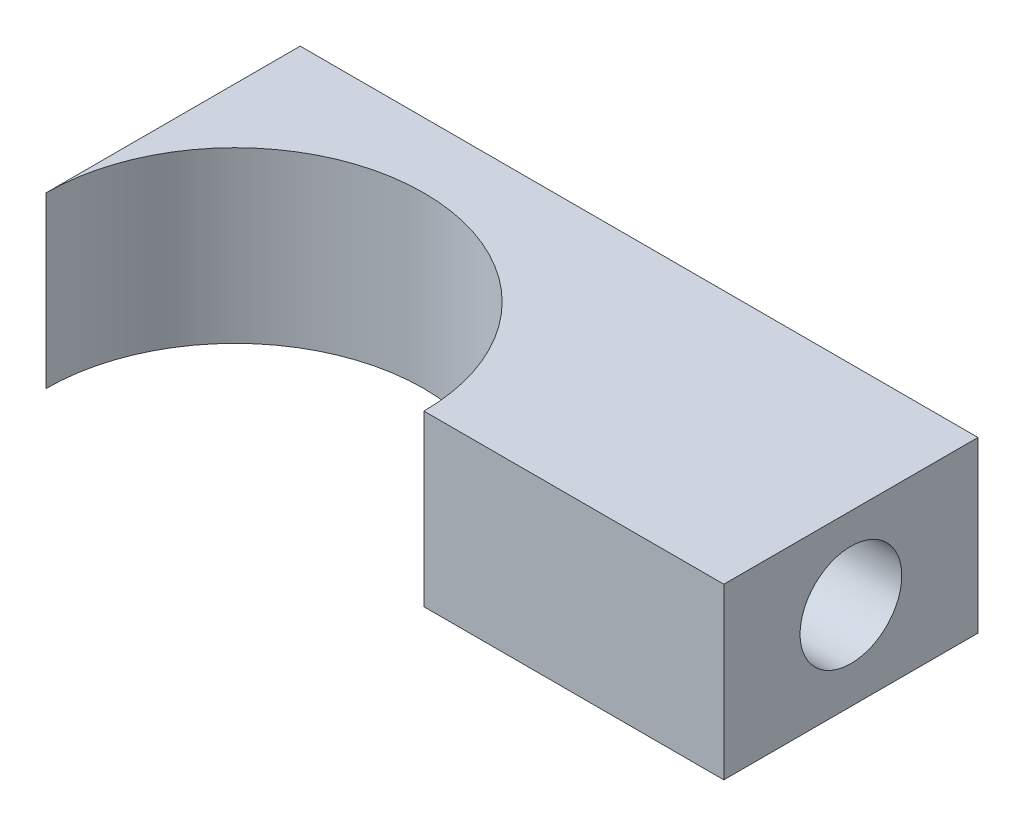
SolidWorks part; units mm, degrees
ref_plane "Ön Düzlem" through (0, 0, 0) normal (0, 0, 1) x (1, 0, 0)
ref_plane "Üst Düzlem" through (0, 0, 0) normal (0, 1, 0) x (1, 0, 0)
ref_plane "Sağ Düzlem" through (0, 0, 0) normal (1, 0, 0) x (0, 0, -1)
sketch "Çizim1" plane through (0, 0, 0) normal (0, 1, 0) x (1, 0, 0)
  line L1 (-20, -7.5) -> (20, -7.5)
  line L2 (-20, -7.5) -> (-20, 7.5)
  line L3 (-20, 7.5) -> (20, 7.5)
  line L4 (20, -7.5) -> (20, 7.5)
  point P4 (0, 7.5)
  point P6 (-20, 0)
  dimension "D1" = 40
  dimension "D2" = 15
extrude "Yükseklik-Ekstrüzyon1" add sketch "Çizim1" along normal blind 10
sketch "Çizim2" plane through (20, 0, 0) normal (1, 0, 0) x (0, 0, -1)
  circle A0 centre (0, 5.1932) radius 3
  dimension "D1" = 6
extrude "Kes-Ekstrüzyon1" cut sketch "Çizim2" against normal blind 10
sketch "Çizim4" plane through (0, 10, 0) normal (0, 1, 0) x (1, 0, 0)
  line L1 (-20, 7.5) -> (-20, -7.5) construction
  circle A0 centre (-8.85, -7.5) radius 11.15
  point P2 (-15, -7.5)
  point P3 (-15, -7.5)
  dimension "D1" = 22.3
extrude "Kes-Ekstrüzyon2" cut sketch "Çizim4" against normal blind 10
